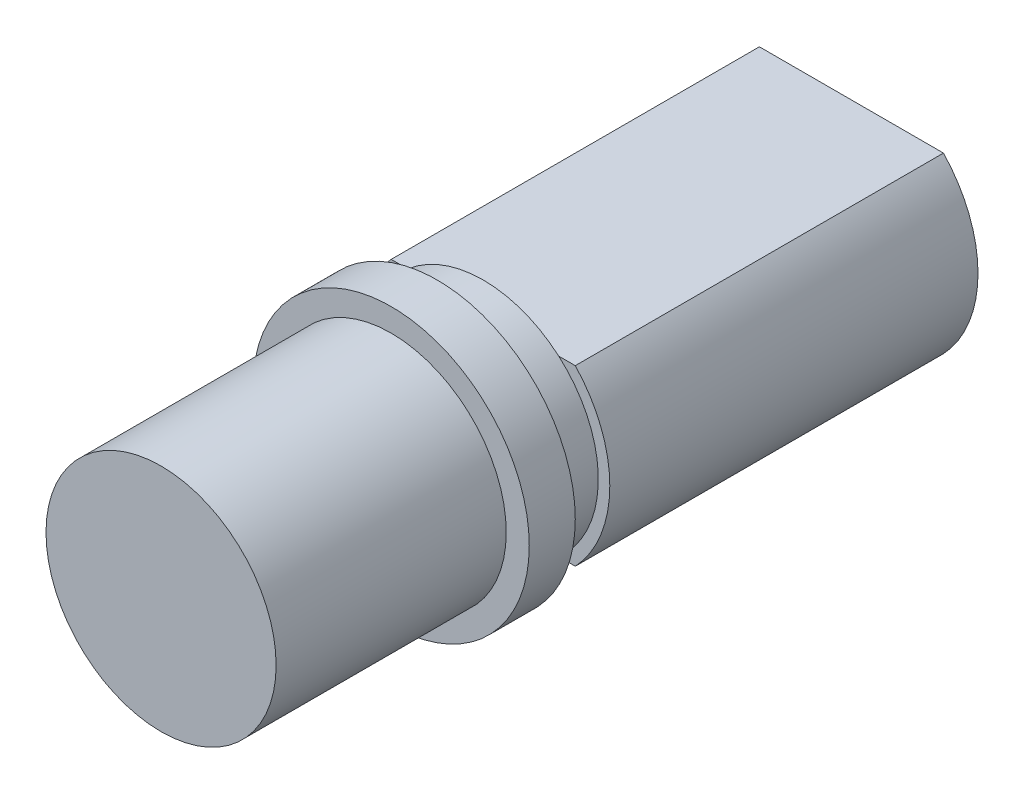
SolidWorks part; units mm, degrees
ref_plane "前视基准面" through (0, 0, 0) normal (0, 0, 1) x (1, 0, 0)
ref_plane "上视基准面" through (0, 0, 0) normal (0, 1, 0) x (1, 0, 0)
ref_plane "右视基准面" through (0, 0, 0) normal (1, 0, 0) x (0, 0, -1)
other "Configuration Table"
sketch "草图1" plane through (0, 0, 0) normal (0, 0, 1) x (1, 0, 0)
  circle A0 centre (0, 0) radius 2.5
  dimension "D1" = 5
extrude "凸台-拉伸1" add sketch "草图1" along normal blind 6.2
sketch "草图2" plane through (0, 0, 0) normal (0, 0, -1) x (-1, 0, 0)
  line L0 (-2, 1.8875) -> (2, 1.8875)
  line L1 (-2, -1.8875) -> (2, -1.8875)
  arc A0 (2, -1.8875) -> (2, 1.8875) centre (0, 0) ccw
  arc A1 (-2, 1.8875) -> (-2, -1.8875) centre (0, 0) ccw
  dimension "D1" = 5.5
  dimension "D2" = 4
  dimension "D3" = 4
extrude "凸台-拉伸2" add sketch "草图2" along normal blind 8
sketch "草图3" plane through (0, 0, 6.2) normal (0, 0, 1) x (1, 0, 0)
  circle A1 centre (0, 0) radius 2.5
  circle A2 centre (0, 0) radius 2.5
  dimension "D1" = 0
extrude "凸台-拉伸3" add sketch "草图3" along normal blind 0.8
sketch "草图4" plane through (0, 0, 0) normal (0, 0, 1) x (1, 0, 0)
  circle A0 centre (0, 0) radius 3
  dimension "D1" = 6
extrude "凸台-拉伸4" add sketch "草图4" along normal blind 1 from offset 1
